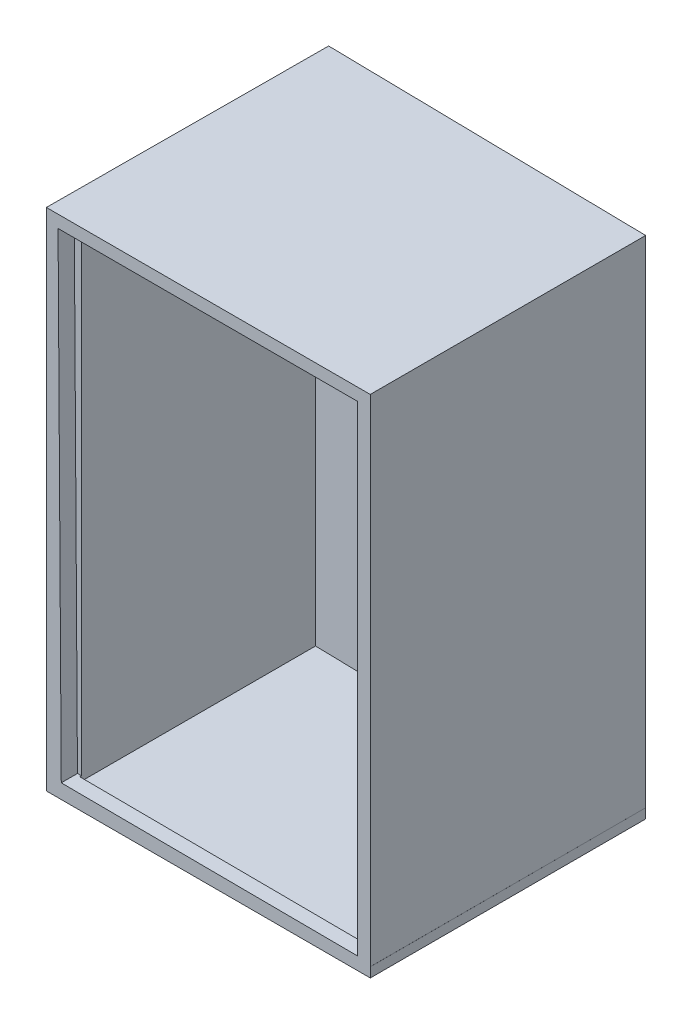
SolidWorks part; units mm, degrees
ref_plane "Front Plane" through (0, 0, 0) normal (0, 0, 1) x (1, 0, 0)
ref_plane "Top Plane" through (0, 0, 0) normal (0, 1, 0) x (1, 0, 0)
ref_plane "Right Plane" through (0, 0, 0) normal (1, 0, 0) x (0, 0, -1)
sketch "Sketch1" plane through (0, 0, 0) normal (0, 1, 0) x (1, 0, 0)
  line L1 (-39.3848, 34.7456) -> (60.6003, 33.016)
  line L2 (-39.3848, 34.7456) -> (-39.3848, -51.984)
  line L3 (-39.3848, -51.984) -> (60.6152, -51.984)
  line L4 (60.6003, 33.016) -> (60.6152, -51.984)
  dimension "D1" = 100
  dimension "D2" = 85
extrude "Boss-Extrude1" add sketch "Sketch1" along normal blind 3
sketch "Sketch2" plane through (0, 3, 0) normal (0, 1, 0) x (1, 0, 0)
  line L1 (-39.3848, 34.7456) -> (60.6003, 33.016)
  line L2 (-39.3848, 34.7456) -> (-39.3848, -51.984)
  line L3 (-39.3848, -51.984) -> (60.5958, -51.984)
  line L4 (60.6003, 33.016) -> (60.5958, -51.984)
  line L5 (-33.5907, 25.3035) -> (54.79, 23.3845)
  line L6 (-33.5907, 25.3035) -> (-33.5907, -47.4974)
  line L7 (-33.5907, -47.4974) -> (54.79, -47.4974)
  line L8 (54.79, 23.3845) -> (54.79, -47.4974)
  point P4 (54.79, 27.6742)
extrude "Boss-Extrude3" add sketch "Sketch2" along normal blind 150
sketch "Sketch4" plane through (0, 153, 0) normal (0, 1, 0) x (1, 0, 0)
  line L1 (-38.9685, 34.7384) -> (60.6003, 33.016)
  line L2 (-38.9685, 34.7384) -> (-39.3848, -51.984)
  line L3 (-39.3848, -51.984) -> (60.5958, -51.984)
  line L4 (60.6003, 33.016) -> (60.5958, -51.984)
  point P4 (60.6003, 33.016)
  point P5 (-39.3848, -51.984)
extrude "Boss-Extrude4" add sketch "Sketch4" along normal blind 3
sketch "Sketch5" plane through (0, 0, 51.984) normal (0, 0, 1) x (1, 0, 0)
  line L1 (-35.7765, 152.1839) -> (56.6541, 152.1839)
  line L2 (-35.7765, 152.1839) -> (-34.7866, 4.4746)
  line L3 (-34.7866, 4.4746) -> (56.6541, 3.9194)
  line L4 (56.6541, 152.1839) -> (56.6541, 3.9194)
  point P4 (-35.7765, 152.1839)
  point P5 (56.6541, 152.1839)
  point P6 (56.6541, 3.9194)
  point P7 (-35.7765, 2.5518)
  point P8 (-34.7866, 4.4746)
extrude "Cut-Extrude1" cut sketch "Sketch5" against normal blind 5
sketch "Sketch6" plane through (0.5333, 0, -24.5626) normal (-0.0217, 0, 0.9998) x (0.9998, 0, 0.0217)
  line L1 (-17.6872, 134.8166) -> (38.1941, 134.8166)
  line L2 (-17.6872, 134.8166) -> (-17.6872, 3.1222)
  line L3 (-17.6872, 3.1222) -> (38.1941, 3.1222)
  line L4 (38.1941, 134.8166) -> (38.1941, 3.1222)
extrude "Cut-Extrude3" cut sketch "Sketch6" against normal blind 19
sketch "Sketch7" plane through (0.5333, 0, -24.5626) normal (-0.0217, 0, 0.9998) x (0.9998, 0, 0.0217)
  line L1 (41.0316, 91.1579) -> (52.8426, 91.1579)
  line L2 (41.0316, 91.1579) -> (41.0316, 34.6027)
  line L3 (41.0316, 34.6027) -> (52.8426, 34.6027)
  line L4 (52.8426, 91.1579) -> (52.8426, 34.6027)
extrude "Boss-Extrude5" add sketch "Sketch7" along normal blind 1
sketch "Sketch8" plane through (0.5116, 0, -23.5628) normal (-0.0217, 0, 0.9998) x (0.9998, 0, 0.0217)
  line L1 (42.3329, 88.4013) -> (51.7635, 88.4013)
  line L2 (42.3329, 88.4013) -> (42.3329, 81.4229)
  line L3 (42.3329, 81.4229) -> (51.7635, 81.4229)
  line L4 (51.7635, 88.4013) -> (51.7635, 81.4229)
extrude "Cut-Extrude4" cut sketch "Sketch8" against normal blind 1
sketch "Sketch9" plane through (0.5116, 0, -23.5628) normal (-0.0217, 0, 0.9998) x (0.9998, 0, 0.0217)
  circle A0 centre (44.2201, 76.9326) radius 2.5535
  circle A1 centre (49.788, 76.9326) radius 2.5274
  circle A2 centre (44.2201, 71.0091) radius 2.4506
  circle A3 centre (49.998, 71.0091) radius 2.3935
  circle A4 centre (46.6051, 64.0436) radius 2.4235
  circle A5 centre (46.6051, 57.2237) radius 2.2184
  circle A6 centre (46.6051, 50.7712) radius 2.3943
  circle A7 centre (46.6051, 43.7755) radius 2.3166
  circle A8 centre (46.6051, 37.7758) radius 2.2498
  point P16 (49.788, 76.9326)
  point P17 (44.2201, 71.0091)
  point P18 (49.998, 71.0091)
  point P19 (47.0283, 57.3912)
  point P20 (46.6051, 57.2237)
  point P21 (46.9079, 50.7364)
  point P22 (46.6051, 50.7712)
  point P23 (46.6051, 37.7758)
  point P24 (46.6051, 43.7755)
extrude "Boss-Extrude6" add sketch "Sketch9" along normal blind 1
sketch "Sketch10" plane through (-17.6831, 0, -0.3839) normal (0.9998, 0, 0.0217) x (0.0217, 0, -0.9998)
  line L1 (28.7065, 141.2863) -> (33.9815, 141.2863)
  line L2 (28.7065, 141.2863) -> (28.7065, 3.1222)
  line L3 (28.7065, 3.1222) -> (33.9815, 3.1222)
  line L4 (33.9815, 141.2863) -> (33.9815, 3.1222)
extrude "Boss-Extrude8" add sketch "Sketch10" along normal blind 28
sketch "Sketch11" plane through (10.3103, 0, 0.2239) normal (0.9998, 0, 0.0217) x (0.0217, 0, -0.9998)
  line L1 (28.8706, 134.8166) -> (34.074, 134.8166)
  line L2 (28.8706, 134.8166) -> (28.8706, 3.1601)
  line L3 (28.8706, 3.1601) -> (34.074, 3.1601)
  line L4 (34.074, 134.8166) -> (34.074, 3.1601)
extrude "Boss-Extrude9" add sketch "Sketch11" along normal blind 28
sketch "Sketch16" plane through (0.4899, 0, -22.5631) normal (-0.0217, 0, 0.9998) x (0.9998, 0, 0.0217)
  text T0 "0"
  point P1 (45.6606, 62.8134)
  point P2 (45.377, 62.1372)
extrude "Boss-Extrude11" add sketch "Sketch16" along normal blind 1
sketch "Sketch17" plane through (0.4899, 0, -22.5631) normal (-0.0217, 0, 0.9998) x (0.9998, 0, 0.0217)
  text T0 "1"
  point P1 (45.2535, 55.4646)
extrude "Boss-Extrude12" add sketch "Sketch17" along normal blind 1
sketch "Sketch18" plane through (0.4899, 0, -22.5631) normal (-0.0217, 0, 0.9998) x (0.9998, 0, 0.0217)
  text T0 "2"
  point P1 (45.4874, 48.9768)
  point P2 (45.2182, 48.9695)
  point P3 (45.3059, 49.1318)
extrude "Boss-Extrude13" add sketch "Sketch18" along normal blind 1
sketch "Sketch19" plane through (0.4899, 0, -22.5631) normal (-0.0217, 0, 0.9998) x (0.9998, 0, 0.0217)
  text T0 "3"
  point P1 (45.1443, 41.9776)
  point P2 (45.4038, 42.0666)
extrude "Boss-Extrude14" add sketch "Sketch19" along normal blind 1
sketch "Sketch20" plane through (0.4899, 0, -22.5631) normal (-0.0217, 0, 0.9998) x (0.9998, 0, 0.0217)
  text T0 "4"
  point P1 (45.5065, 35.9651)
  point P2 (44.7313, 35.607)
  point P3 (0, 0)
  point P4 (44.6777, 35.7964)
  point P5 (44.342, 36.0284)
  point P6 (44.9979, 35.9816)
extrude "Boss-Extrude16" add sketch "Sketch20" along normal blind 1
sketch "Sketch21" plane through (0.4899, 0, -22.5631) normal (-0.0217, 0, 0.9998) x (0.9998, 0, 0.0217)
  text T0 "G"
  point P1 (47.8552, 69.1012)
extrude "Boss-Extrude17" add sketch "Sketch21" along normal blind 1
sketch "Sketch22" plane through (0.4899, 0, -22.5631) normal (-0.0217, 0, 0.9998) x (0.9998, 0, 0.0217)
  text T0 "E"
extrude "Boss-Extrude18" add sketch "Sketch22" along normal blind 1
sketch "Sketch23" plane through (0.4899, 0, -22.5631) normal (-0.0217, 0, 0.9998) x (0.9998, 0, 0.0217)
  line L0 (48.6108, 75.931) -> (50.7684, 75.9466)
  line L1 (49.3914, 75.7453) -> (50.051, 75.7453)
  arc A0 (50.1532, 78.2413) -> (49.3376, 78.2413) centre (49.7454, 78.2174) ccw
  arc A1 (50.1532, 78.2413) -> (49.3376, 78.2413) centre (49.7454, 77.068) ccw
  arc A2 (50.4844, 77.8979) -> (48.9579, 77.8979) centre (49.7212, 77.1809) ccw
  spline S0 degree 3 poles (48.9579, 77.8979) (49.1595, 77.254) (49.0294, 76.4702) (48.6108, 75.931) knots 0 0 0 0 1 1 1 1
  spline S1 degree 2 poles (50.4844, 77.8979) (50.2873, 76.8896) (50.7684, 75.9466) knots 0 0 0 1 1 1
  spline S2 degree 2 poles (49.3914, 75.7453) (49.749, 75.0793) (50.051, 75.7453) knots 0 0 0 1 1 1
  point P3 (49.3508, 78.3065)
  point P16 (49.7487, 75.4129)
  point P17 (50.1741, 78.2784)
  point P18 (49.3376, 78.2413)
  point P19 (50.1532, 78.2413)
extrude "Boss-Extrude19" add sketch "Sketch23" along normal blind 1
sketch "Sketch24" plane through (0.4899, 0, -22.5631) normal (-0.0217, 0, 0.9998) x (0.9998, 0, 0.0217)
  circle A0 centre (44.0951, 76.955) radius 0.2073
  spline S0 degree 3 poles (42.0285, 78.3933) (44.2258, 76.7807) (43.7026, 78.0411) (44.7685, 78.8686) (42.0285, 78.3933) (44.2258, 76.7807) (43.7026, 78.0411) knots -0.813543 -0.651527 -0.316943 0 0.186457 0.348473 0.683057 1 1.186457 1.348473 1.683057 only from (43.8878, 77.2916) to (43.8878, 77.2916)
  spline S1 degree 3 poles (46.9458, 77.3405) (43.7973, 77.3299) (45.138, 76.8114) (44.6328, 75.565) (46.9458, 77.3405) (43.7973, 77.3299) (45.138, 76.8114) knots -0.844516 -0.680385 -0.361491 0 0.155484 0.319615 0.638509 1 1.155484 1.319615 1.638509 only from (44.471, 77.1381) to (44.471, 77.1381)
  spline S2 degree 3 poles (43.1264, 74.5865) (44.4811, 76.9764) (43.384, 76.3105) (42.423, 77.5351) (43.1264, 74.5865) (44.4811, 76.9764) (43.384, 76.3105) knots -0.86209 -0.657393 -0.312988 0 0.13791 0.342607 0.687012 1 1.13791 1.342607 1.687012 only from (44.0457, 76.6289) to (44.0457, 76.6289)
  point P4 (43.2371, 76.4495)
extrude "Boss-Extrude20" add sketch "Sketch24" along normal blind 1
sketch "Sketch25" plane through (0.5333, 0, -24.5626) normal (-0.0217, 0, 0.9998) x (0.9998, 0, 0.0217)
  line L0 (48.0014, 86.2825) -> (49.5642, 86.2825)
  line L1 (49.5642, 86.2825) -> (49.5642, 83.7885)
  line L2 (49.5642, 83.7885) -> (50.3013, 83.7885)
  line L3 (50.3013, 83.7885) -> (48.7828, 82.3619)
  line L4 (48.7828, 82.3619) -> (47.4426, 83.7885)
  line L5 (47.4426, 83.7885) -> (48.0014, 83.7885)
  line L6 (48.0014, 83.7885) -> (48.0014, 86.2825)
  text T0 "E"
extrude "Boss-Extrude21" add sketch "Sketch25" along normal blind 1
